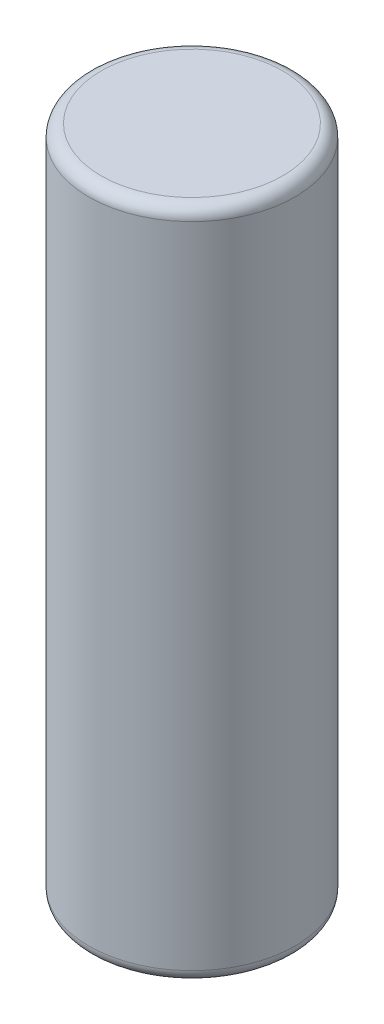
SolidWorks part; units mm, degrees
ref_plane "Front Plane" through (0, 0, 0) normal (0, 0, 1) x (1, 0, 0)
ref_plane "Top Plane" through (0, 0, 0) normal (0, 1, 0) x (1, 0, 0)
ref_plane "Right Plane" through (0, 0, 0) normal (1, 0, 0) x (0, 0, -1)
sketch "Sketch1" plane through (0, 0, 0) normal (0, 1, 0) x (1, 0, 0)
  circle A0 centre (0, 0) radius 10.7
  dimension "D1" = 21.4
extrude "Boss-Extrude1" add sketch "Sketch1" along normal blind 69.85
fillet "Fillet1" radius 1.27 2 edges at (0, 0, 10.7) (0, 69.85, 10.7)
